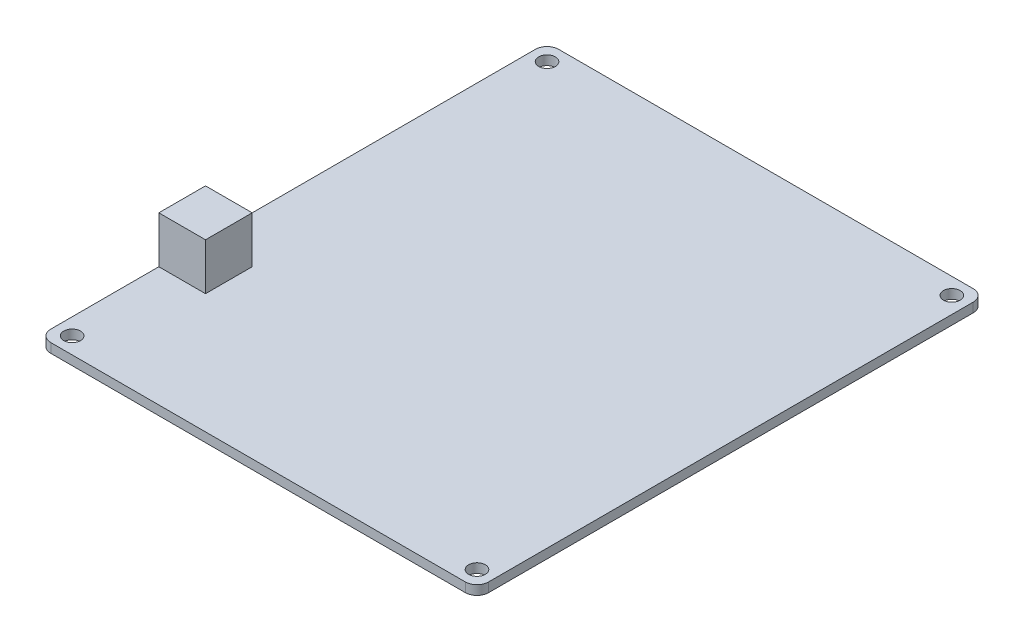
SolidWorks part; units mm, degrees
ref_plane "Front Plane" through (0, 0, 0) normal (0, 0, 1) x (1, 0, 0)
ref_plane "Top Plane" through (0, 0, 0) normal (0, 1, 0) x (1, 0, 0)
ref_plane "Right Plane" through (0, 0, 0) normal (1, 0, 0) x (0, 0, -1)
sketch "Sketch1" plane through (0, 0, 0) normal (0, 1, 0) x (1, 0, 0)
  line L1 (-37.5, -43.5) -> (37.5, -43.5)
  line L2 (-37.5, -43.5) -> (-37.5, 43.5)
  line L3 (-37.5, 43.5) -> (37.5, 43.5)
  line L4 (37.5, -43.5) -> (37.5, 43.5)
  line L5 (-37.5, -43.5) -> (37.5, 43.5) construction
  line L6 (-37.5, 43.5) -> (37.5, -43.5) construction
  point P0 (0, 0)
  dimension "D1" = 87
  dimension "D2" = 75
extrude "Boss-Extrude1" add sketch "Sketch1" along normal blind 1.6 contours L4 L3 L2 L1
sketch "Sketch2" plane through (0, 1.6, 0) normal (0, 1, 0) x (1, 0, 0)
  line L1 (-37.5, 43.5) -> (37.5, 43.5) construction
  line L2 (-37.5, -43.5) -> (-37.5, 43.5) construction
  circle A0 centre (-34.67, 40.67) radius 1.43
  dimension "D1" = 2.86
  dimension "D2" = 2.83
  dimension "D3" = 2.83
extrude "Cut-Extrude1" cut sketch "Sketch2" against normal through all
mirror "Mirror1" about plane through (0, 0, 0) normal (0, 0, 1) of "Cut-Extrude1" second plane through (0, 0, 0) second plane normal (1, 0, 0)
fillet "Fillet1" radius 2 4 edges at (37.5, 0.8, 43.5) (-37.5, 0.8, 43.5) (37.5, 0.8, -43.5) (-37.5, 0.8, -43.5)
sketch "Sketch3" plane through (0, 1.6, 0) normal (0, 1, 0) x (1, 0, 0)
  line L0 (-37.5, -41.5) -> (-37.5, 41.5) construction
  line L1 (-29.5, -23) -> (-37.5, -23)
  line L2 (-29.5, -23) -> (-29.5, -15)
  line L3 (-29.5, -15) -> (-37.5, -15)
  line L4 (-37.5, -23) -> (-37.5, -15)
  line L5 (-29.5, -23) -> (-37.5, -15) construction
  line L6 (-29.5, -15) -> (-37.5, -23) construction
  line L7 (-35.5, -43.5) -> (35.5, -43.5) construction
  point P0 (-33.5, -19)
  dimension "D1" = 20.5
  dimension "D2" = 8
  dimension "D3" = 8
extrude "Boss-Extrude2" add sketch "Sketch3" along normal blind 8
